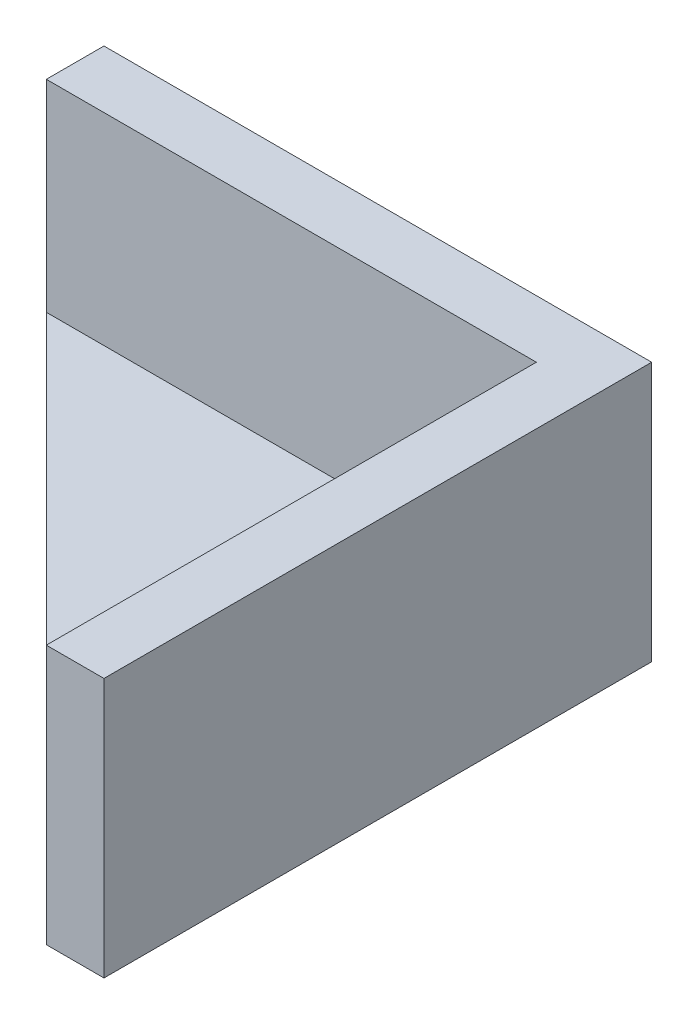
SolidWorks part; units mm, degrees
ref_plane "前视基准面" through (0, 0, 0) normal (0, 0, 1) x (1, 0, 0)
ref_plane "上视基准面" through (0, 0, 0) normal (0, 1, 0) x (1, 0, 0)
ref_plane "右视基准面" through (0, 0, 0) normal (1, 0, 0) x (0, 0, -1)
sketch "草图1" plane through (0, 0, 0) normal (0, 0, 1) x (1, 0, 0)
  line L1 (-19, -9) -> (19, -9)
  line L2 (-19, -9) -> (-19, 9)
  line L3 (-19, 9) -> (19, 9)
  line L4 (19, -9) -> (19, 9)
  point P0 (0, 0)
extrude "凸台-拉伸1" add sketch "草图1" along normal blind 4
sketch "草图2" plane through (0, 0, 4) normal (0, 0, 1) x (1, 0, 0)
  line L0 (19, 9) -> (19, -9)
  line L3 (15, -5) -> (15, 9)
  line L4 (19, 9) -> (-19, 9) construction
  line L5 (15, 9) -> (19, 9)
  line L6 (-19, -9) -> (-19, -5)
  line L7 (-19, 9) -> (-19, -9) construction
  line L8 (-19, -5) -> (15, -5)
  line L9 (-19, -9) -> (19, -9)
extrude "凸台-拉伸3" add sketch "草图2" along normal blind 34
sketch "草图4" plane through (0, -5, 0) normal (0, 1, 0) x (1, 0, 0)
  line L0 (15, -38) -> (-19, -4)
  line L1 (-19, -4) -> (-19, -38)
  line L2 (-19, -38) -> (15, -38)
extrude "切除-拉伸1" cut sketch "草图4" against normal blind 34
